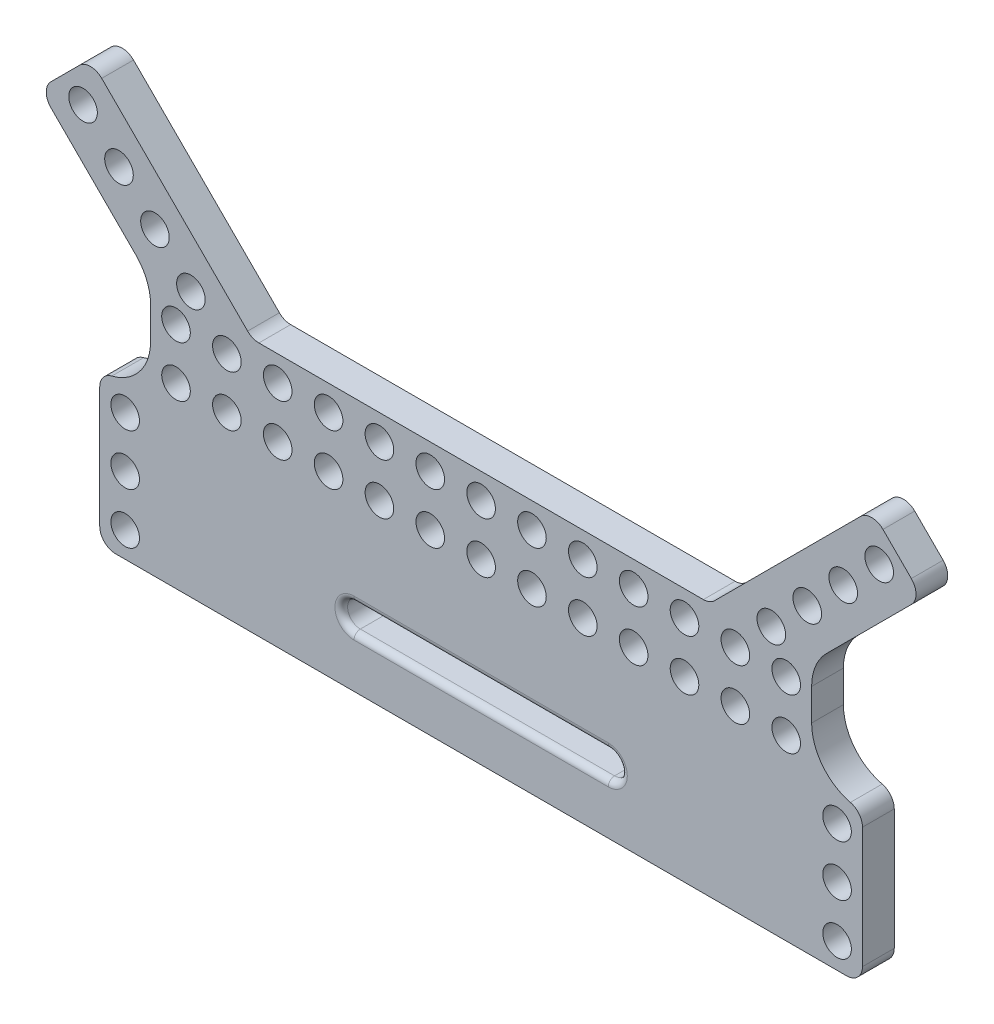
SolidWorks part; units mm, degrees
ref_plane "前视基准面" through (0, 0, 0) normal (0, 0, 1) x (1, 0, 0)
ref_plane "上视基准面" through (0, 0, 0) normal (0, 1, 0) x (1, 0, 0)
ref_plane "右视基准面" through (0, 0, 0) normal (1, 0, 0) x (0, 0, -1)
sketch "草图1" plane through (0, 0, 0) normal (0, 0, 1) x (1, 0, 0)
  line L0 (0, 0) -> (0, 30336.2514) construction
  line L1 (-60, 20) -> (-52, 20) construction
  line L2 (-60, 4) -> (-60, -20)
  line L3 (-60, -20) -> (60, -20)
  line L4 (60, 4) -> (60, -20)
  line L5 (-60, 20) -> (60, -20) construction
  line L6 (-60, -20) -> (60, 20) construction
  line L7 (20, -8) -> (-20, -8)
  line L8 (-20, -12) -> (20, -12)
  line L9 (-48, 16) -> (-49.591, 17.591) construction
  line L10 (-69.4558, 37.4558) -> (-61.4558, 45.4558)
  line L11 (-61.4558, 45.4558) -> (-36, 20)
  line L12 (-40, 16) -> (-45.6569, 21.6569) construction
  line L13 (-56, -16) -> (-56, -8) construction
  line L14 (-56, 16) -> (-48, 16) construction
  line L15 (-44, 20) -> (-36, 20) construction
  line L16 (-40, 16) -> (-63.2758, 39.2758) construction
  line L17 (-36, 20) -> (36, 20)
  line L18 (-52, 20) -> (-47.1791, 20) construction
  line L19 (-44.1346, 20) -> (-44, 20)
  line L20 (-47.1791, 20) -> (-44.1346, 20) construction
  line L21 (-49.591, 17.591) -> (-52, 20) construction
  line L22 (-52, 20) -> (-69.4558, 37.4558)
  line L23 (-36, 20) -> (-33.591, 17.591) construction
  line L24 (-33.591, 17.591) -> (-32, 16) construction
  line L25 (52, 20) -> (69.4558, 37.4558)
  line L26 (69.4558, 37.4558) -> (61.4558, 45.4558)
  line L27 (61.4558, 45.4558) -> (36, 20)
  line L28 (36, 20) -> (44.1346, 20) construction
  line L29 (44.1346, 20) -> (47.1791, 20) construction
  line L30 (47.1791, 20) -> (52, 20) construction
  line L31 (52, 20) -> (60, 20) construction
  line L32 (-52, 20) -> (-52, 4)
  line L33 (-52, 4) -> (-60, 4)
  line L34 (52, 4) -> (60, 4)
  line L35 (52, 20) -> (52, 4)
  line L36 (-60, 20) -> (-60, 4) construction
  line L37 (60, 20) -> (60, 4) construction
  arc A0 (-20, -8) -> (-20, -12) centre (-20, -10) ccw
  arc A1 (20, -8) -> (20, -12) centre (20, -10) cw
  circle A2 centre (-56, -16) radius 2.25
  circle A3 centre (-56, -8) radius 2.25
  circle A4 centre (-56, 0) radius 2.25
  circle A5 centre (-56, 8) radius 2.25 construction
  circle A6 centre (-56, 16) radius 2.25 construction
  circle A7 centre (56, 16) radius 2.25 construction
  circle A8 centre (56, 8) radius 2.25 construction
  circle A9 centre (56, 0) radius 2.25
  circle A10 centre (56, -16) radius 2.25
  circle A11 centre (56, -8) radius 2.25
  circle A12 centre (-48, 16) radius 2.25
  circle A13 centre (-48, 8) radius 2.25
  circle A14 centre (-40, 16) radius 2.25
  circle A15 centre (-40, 8) radius 2.25
  circle A16 centre (-32, 16) radius 2.25
  circle A17 centre (-32, 8) radius 2.25
  circle A18 centre (-24, 16) radius 2.25
  circle A19 centre (-24, 8) radius 2.25
  circle A20 centre (-16, 16) radius 2.25
  circle A21 centre (-16, 8) radius 2.25
  circle A22 centre (-8, 16) radius 2.25
  circle A23 centre (-8, 8) radius 2.25
  circle A24 centre (0, 16) radius 2.25
  circle A25 centre (0, 8) radius 2.25
  circle A26 centre (8, 16) radius 2.25
  circle A27 centre (8, 8) radius 2.25
  circle A28 centre (16, 16) radius 2.25
  circle A29 centre (16, 8) radius 2.25
  circle A30 centre (24, 16) radius 2.25
  circle A31 centre (24, 8) radius 2.25
  circle A32 centre (32, 16) radius 2.25
  circle A33 centre (32, 8) radius 2.25
  circle A34 centre (40, 16) radius 2.25
  circle A35 centre (40, 8) radius 2.25
  circle A36 centre (48, 16) radius 2.25
  circle A37 centre (48, 8) radius 2.25
  circle A38 centre (-45.6569, 21.6569) radius 2.25
  circle A39 centre (-51.3137, 27.3137) radius 2.25
  circle A40 centre (-56.9706, 32.9706) radius 2.25
  circle A41 centre (-62.6274, 38.6274) radius 2.25
  circle A42 centre (45.6569, 21.6569) radius 2.25
  circle A43 centre (51.3137, 27.3137) radius 2.25
  circle A44 centre (56.9706, 32.9706) radius 2.25
  circle A45 centre (62.6274, 38.6274) radius 2.25
  point P0 (0, 0)
  dimension "D1" = 20
  dimension "D5" = 2
  dimension "D7" = 4
  dimension "D8" = 4.5
  dimension "D2" = 120
  dimension "D3" = 40
  dimension "D4" = 10
  dimension "D6" = 4
  dimension "D10" = 8
  dimension "D12" = 8
  dimension "D13" = 135
  dimension "D14" = 5
  dimension "D15" = 8
  dimension "D16" = 4
  dimension "D17" = 4
  dimension "D9" = 5
  dimension "D11" = 14
extrude "凸台-拉伸1" add sketch "草图1" along normal blind 5
fillet "圆角1" radius 2.5 10 edges at (60, -20, 2.5) (-60, -20, 2.5) (-61.4558, 45.4558, 2.5) (-69.4558, 37.4558, 2.5) (-36, 20, 2.5) (36, 20, 2.5) (61.4558, 45.4558, 2.5) (69.4558, 37.4558, 2.5) (60, 4, 2.5) (-60, 4, 2.5)
fillet "圆角2" radius 1 4 edges at (0, -8, 5) (-22, -10, 5) (0, -12, 5) (22, -10, 5)
fillet "圆角3" radius 8 4 edges at (-52, 4, 2.5) (-52, 20, 2.5) (52, 4, 2.5) (52, 20, 2.5)
